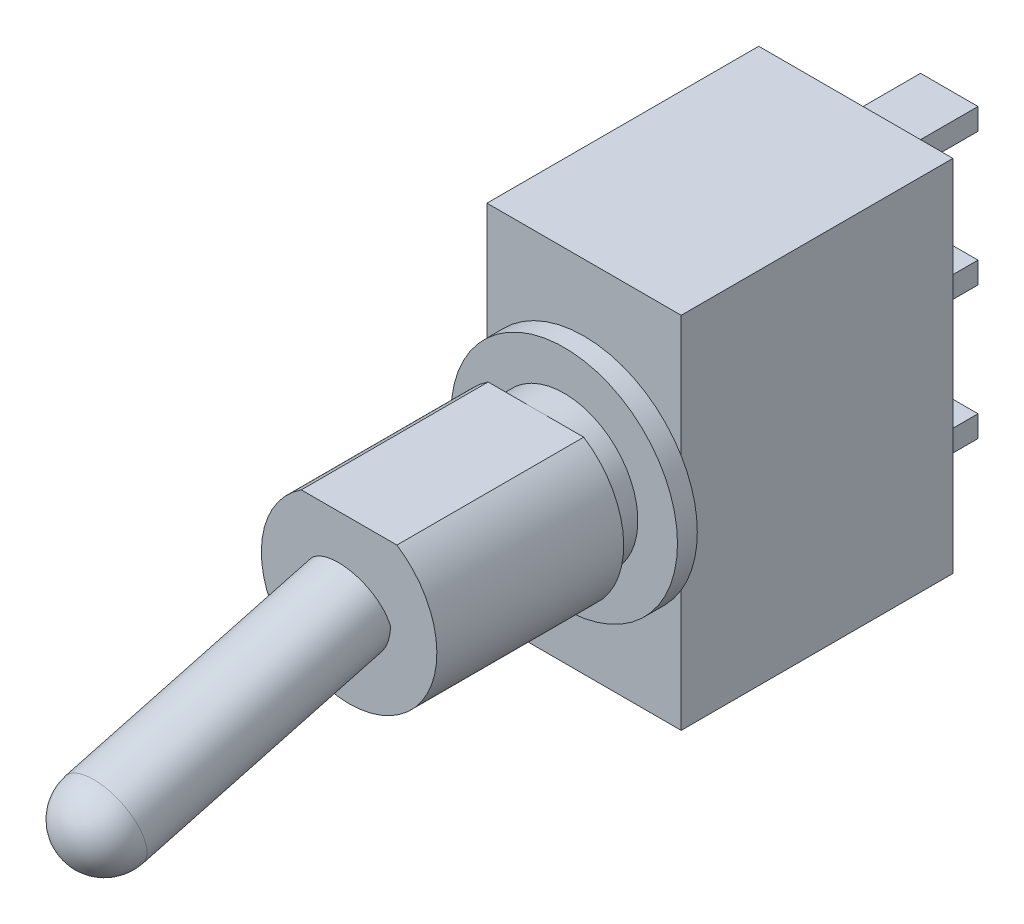
SolidWorks part; units mm, degrees
ref_plane "Plan de face" through (0, 0, 0) normal (0, 0, 1) x (1, 0, 0)
ref_plane "Plan de dessus" through (0, 0, 0) normal (0, 1, 0) x (1, 0, 0)
ref_plane "Plan de droite" through (0, 0, 0) normal (1, 0, 0) x (0, 0, -1)
sketch "Esquisse1" plane through (0, 0, 0) normal (0, 0, 1) x (1, 0, 0)
  line L1 (-3.43, 6.35) -> (3.43, 6.35)
  line L2 (-3.43, 6.35) -> (-3.43, -6.35)
  line L3 (-3.43, -6.35) -> (3.43, -6.35)
  line L4 (3.43, 6.35) -> (3.43, -6.35)
  line L5 (-3.43, 6.35) -> (3.43, -6.35) construction
  line L6 (-3.43, -6.35) -> (3.43, 6.35) construction
  point P0 (0, 0)
  dimension "D1" = 12.7
  dimension "D2" = 6.86
extrude "Boss.-Extru.1" add sketch "Esquisse1" along normal blind 9.6
sketch "Sketch1" plane through (0, 0, 9.6) normal (0, 0, -1) x (-1, 0, 0)
  circle A0 centre (0, 0) radius 4
  dimension "D1" = 8
extrude "Boss-Extrude1" add sketch "Sketch1" against normal blind 0.7
sketch "Sketch2" plane through (0, 0, 0) normal (1, 0, 0) x (0, 0, -1)
  line L0 (0, 0) -> (-24.5076, 0) construction
  line L1 (-10.3, 2.6) -> (-11.3, 2.6)
  line L2 (-10.3, 4) -> (-10.3, -4) construction
  line L3 (-11.3, 2.6) -> (-11.3, 3.1)
  line L4 (-11.3, 3.1) -> (-17.9, 3.1)
  line L5 (-17.9, 3.1) -> (-17.9, 0)
  line L6 (-17.9, 0) -> (-10.3, 0)
  line L7 (-10.3, 0) -> (-10.3, 2.6)
  dimension "D1" = 5.2
  dimension "D2" = 6.2
  dimension "D3" = 7.6
  dimension "D4" = 1
revolve "Revolve1" add sketch "Sketch2" angle 360 about L0
sketch "Esquisse3" plane through (0, 0, 0) normal (1, 0, 0) x (0, 0, -1)
  line L0 (-17.9, 0) -> (-39.0868, -5.677) construction
  line L2 (0, 0) -> (-25.0079, 0) construction
  line L3 (-26.9229, -0.9062) -> (-18.2779, 1.4103)
  line L4 (-18.2779, 1.4103) -> (-17.9, 0)
  line L5 (-17.9, 0) -> (-27.9553, -2.6943)
  line L6 (-17.9, 3.1) -> (-17.9, -3.1) construction
  arc A0 (-27.9553, -2.6943) -> (-26.9229, -0.9062) centre (-26.545, -2.3164) cw
  point P0 (-2.9496, -1.3334)
  point P2 (0, 0)
  point P7 (0, 0)
  point P13 (8.1643, -0.1944)
  dimension "D1" = 15
  dimension "D2" = 2.92
  dimension "D3" = 10.41
revolve "Révolution1" add sketch "Esquisse3" angle 360 about L0
sketch "Esquisse4" plane through (0, 0, 0) normal (0, 0, 1) x (1, 0, 0)
  line L1 (-1.015, 0.38) -> (1.015, 0.38)
  line L2 (-1.015, 0.38) -> (-1.015, -0.38)
  line L3 (-1.015, -0.38) -> (1.015, -0.38)
  line L4 (1.015, 0.38) -> (1.015, -0.38)
  line L5 (-1.015, 0.38) -> (1.015, -0.38) construction
  line L6 (-1.015, -0.38) -> (1.015, 0.38) construction
  line L7 (-1.015, 5.08) -> (1.015, 5.08)
  line L8 (-1.015, 5.08) -> (-1.015, 4.32)
  line L9 (-1.015, 4.32) -> (1.015, 4.32)
  line L10 (1.015, 5.08) -> (1.015, 4.32)
  line L11 (-1.015, 5.08) -> (1.015, 4.32) construction
  line L12 (-1.015, 4.32) -> (1.015, 5.08) construction
  line L13 (-1.015, -4.32) -> (1.015, -4.32)
  line L14 (-1.015, -4.32) -> (-1.015, -5.08)
  line L15 (-1.015, -5.08) -> (1.015, -5.08)
  line L16 (1.015, -4.32) -> (1.015, -5.08)
  line L17 (-1.015, -4.32) -> (1.015, -5.08) construction
  line L18 (-1.015, -5.08) -> (1.015, -4.32) construction
  point P0 (0, 0)
  point P5 (0, 4.7)
  point P11 (0, -4.7)
  dimension "D1" = 0.76
  dimension "D2" = 2.03
  dimension "D3" = 0.76
  dimension "D4" = 2.03
  dimension "D5" = 0.76
  dimension "D6" = 2.03
  dimension "D7" = 4.7
  dimension "D8" = 4.7
extrude "Boss.-Extru.3" add sketch "Esquisse4" against normal blind 3.3
sketch "Sketch3" plane through (0, 0, 17.9) normal (0, 0, 1) x (1, 0, 0)
  line L1 (-3.1839, 2.6) -> (3.6492, 2.6)
  line L2 (-3.1839, 2.6) -> (-3.1839, 5.5022)
  line L3 (-3.1839, 5.5022) -> (3.6492, 5.5022)
  line L4 (3.6492, 2.6) -> (3.6492, 5.5022)
  circle A0 centre (0, 0) radius 2.6 construction
extrude "Cut-Extrude1" cut sketch "Sketch3" against normal up to surface (7.6 mm away) up to face at (-2.6, 0, 10.3)
